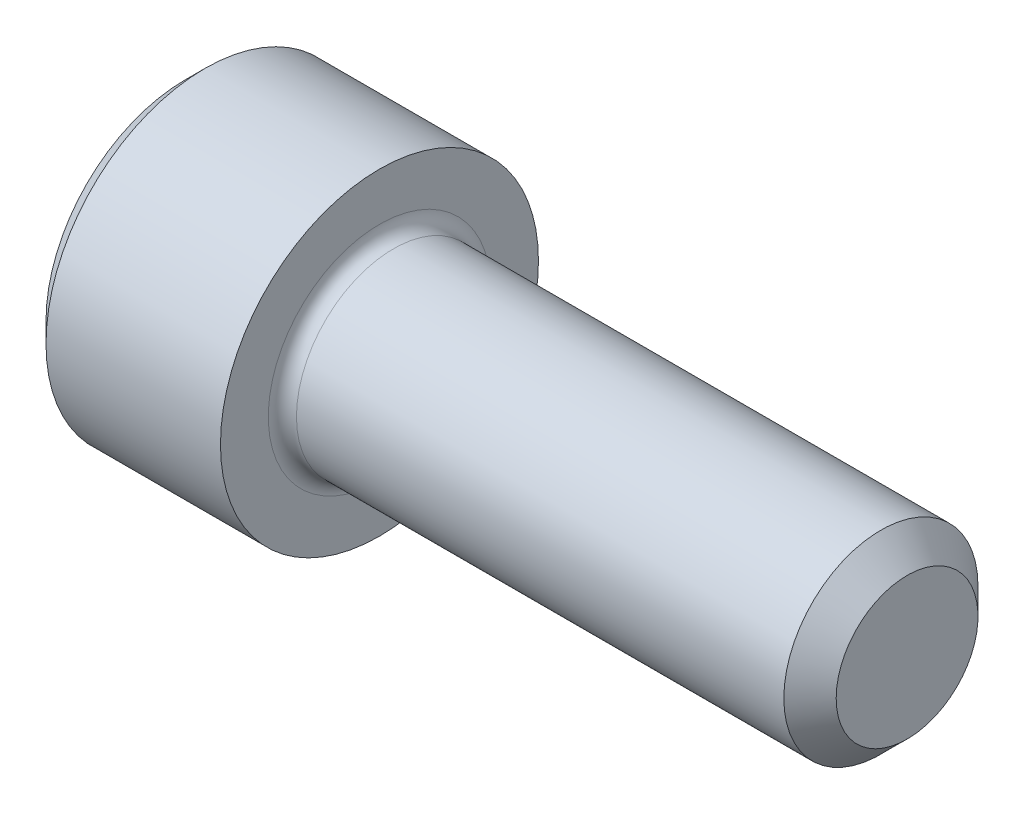
SolidWorks part; units mm, degrees
revolve "Base-Revolve" add sketch "BodySke"
sketch "BodySke" plane through (0, 0, 0) normal (0, 0, 1) x (1, 0, 0)
  line L0 (0, 0) -> (0, 2.5146)
  line L1 (0.3556, 2.8702) -> (3.5052, 2.8702)
  line L2 (3.5052, 2.8702) -> (3.5052, 1.7526)
  line L3 (3.5052, 1.7526) -> (12.5578, 1.7526)
  line L4 (13.0302, 1.2802) -> (13.0302, 0)
  line L5 (13.0302, 0) -> (0, 0)
  line L6 (-31.75, 0) -> (127, 0) construction
  line L7 (0, 2.5146) -> (0.3556, 2.8702)
  line L8 (13.0302, 1.2802) -> (12.5578, 1.7526)
  line L9 (0, -2.5146) -> (0.3556, -2.8702) construction
  line L10 (13.0302, -1.2802) -> (12.5578, -1.7526) construction
  line L11 (4.2977, 9.525) -> (4.2977, 3.175) construction
  line L12 (3.5052, 9.525) -> (3.5052, 3.175) construction
  line L13 (-25.0698, 9.525) -> (-25.0698, 3.175) construction
  dimension "Diameter" = 3.5052
  dimension "Head_ht" = 3.5052
  dimension "Length" = 9.525
  dimension "Body_ch_ang" = 45
  dimension "Head_dia" = 5.7404
  dimension "Head_ch_ang" = 45
  dimension "Head_side_ht" = 3.1496
  dimension "Minor_dia" = 2.5603
  dimension "Advance" = 0.7925
  dimension "Thread_nom" = 9.525
  dimension "Thread_length" = 38.1
cosmetic thread "ThreadCosmetic" [suppressed]
fillet "Fillet1" radius 0.254 1 edges at (3.5052, 0, 1.7526)
ref_plane "Plane1" through (0, 0, 0) normal (0, 0, 1) x (1, 0, 0)
ref_plane "Plane2" through (0, 0, 0) normal (0, 1, 0) x (1, 0, 0)
ref_plane "Plane3" through (0, 0, 0) normal (1, 0, 0) x (0, 0, -1)
sketch "Sketch2" plane through (0, 0, 0) normal (0, 0, 1) x (1, 0, 0)
  line L0 (0, 1.3843) -> (1.6256, 1.3843)
  line L1 (1.6256, 1.3843) -> (2.4248, 0)
  line L2 (-31.75, 0) -> (127, 0) construction
  line L3 (2.4248, 0) -> (0, 0)
  line L4 (0, 0) -> (0, 1.3843)
  line L5 (0, 2.5146) -> (0, -2.5146) construction
  line L6 (0, 0) -> (47.625, 0) construction
  line L7 (3.5052, -2.8702) -> (3.5052, 2.8702) construction
  dimension "D1" = 1.3843
  dimension "D2" = 60
revolve "Hex-PreBroach" cut sketch "Sketch2" angle 360 about L6
sketch "Sketch3" plane through (0, 0, 0) normal (-1, 0, 0) x (0, 0.5, 0.866)
  line L0 (0.7992, 1.3843) -> (-0.7992, 1.3843)
  line L1 (-0.7992, 1.3843) -> (-1.5985, 0)
  line L2 (0.7992, 1.3843) -> (1.5985, 0)
  line L3 (0.7992, -1.3843) -> (1.5985, 0)
  line L4 (0.7992, -1.3843) -> (-0.7992, -1.3843)
  line L5 (-0.7992, -1.3843) -> (-1.5985, 0)
  dimension "D1" = 1.3843
  dimension "D2" = 1.3843
  dimension "Hex_size" = 2.7686
extrude "Hex" cut sketch "Sketch3" against normal blind 1.6256
sketch "Sketch4" plane through (0, 0, 0) normal (-1, 0, 0) x (0, 0, 1)
  line L0 (0, 0) -> (1.7399, 0)
  line L1 (0, 0) -> (6.1484, 3.5498) construction
  line L2 (0, 0) -> (0.8699, 1.5068)
  line L3 (1.4457, 0.3947) -> (1.6607, 0.5189)
  line L4 (1.0647, 1.0546) -> (1.2797, 1.1788)
  arc A0 (1.4457, 0.3947) -> (1.0647, 1.0546) centre (0, 0) ccw
  arc A1 (1.7399, 0) -> (1.6607, 0.5189) centre (0, 0) ccw
  arc A2 (0.8699, 1.5068) -> (1.2797, 1.1788) centre (0, 0) cw
  dimension "D1" = 30
  dimension "D2" = 60
  dimension "Spline_p_dim" = 0.762
  dimension "D3" = 0.381
extrude "Spline" [suppressed] cut sketch "Sketch4" against normal blind 1.6256
pattern_circular "CirPattern1" [suppressed] count 6 every 60
sketch "Sketch5" plane through (0, 0, 0) normal (0, 0, 1) x (1, 0, 0)
  line L0 (-31.75, 0) -> (127, 0) construction
  line L2 (0, 2.5146) -> (0, -2.5146) construction
  circle A0 centre (1.27, 0) radius 0.4445
  dimension "Drilled_hole_dia" = 0.889
  dimension "Drilled_hole_loc" = 1.27
extrude "Hole" [suppressed] cut sketch "Sketch5" against normal through all and the other way through all
pattern_circular "Drilled-4" [suppressed] count 2 every 60
pattern_circular "Drilled-6" [suppressed] count 3 every 60
sketch "ThdSchSke" plane through (0, 0, 0) normal (0, 0, 1) x (1, 0, 0)
  line L0 (4.2977, -1.2802) -> (3.9669, -1.7526)
  line L1 (4.2977, -1.2802) -> (4.6285, -1.7526)
  line L2 (4.6285, -1.7526) -> (4.6285, -2.1907)
  line L3 (-3.175, 0) -> (5.1513, 0) construction
  line L5 (4.6285, -2.1907) -> (3.9669, -2.1907)
  line L6 (3.9669, -2.1907) -> (3.9669, -1.7526)
  line L7 (0, 2.5146) -> (0, -2.5146) construction
  dimension "Thread_minor" = 2.5603
  dimension "Diameter" = 3.5052
  dimension "Start" = 4.2977
revolve "ThreadSchematic" [suppressed] cut sketch "ThdSchSke" angle 360 about L3
pattern_linear "ThdSchPat" [suppressed]
equation "\"D2@Sketch3\" = \"Hex_size@Sketch3\" / 2"
equation "\"D1@Sketch3\" = \"Hex_size@Sketch3\" / 2"
equation "\"D1@Sketch2\" = \"Hex_size@Sketch3\" / 2"
equation "\"D3@Sketch4\" = \"Spline_p_dim@Sketch4\" / 2"
equation "\"Thread_minor@ThreadCosmetic\"  =  \"Minor_dia@BodySke\""
equation "\"D2@CirPattern1\" = 360 / \"Num_teeth@CirPattern1\""
equation "\"Wall_thickness@Sketch2\" = \"Head_ht@BodySke\" - \"Key_eng@Hex\""
equation "\"Thread_length@ThreadCosmetic\" = ((sgn( (\"Length@BodySke\" - \"Advance@BodySke\" ) - \"Thread_nom@BodySke\" )-1)*( (\"Length@BodySke\" - \"Advance@BodySke\" ) - \"Thread_nom@BodySke\" ))/-2+ \"Thread_nom@BodySke\""
equation "\"Thread_minor@ThdSchSke\" = \"Minor_dia@BodySke\""
equation "\"Diameter@ThdSchSke\" = \"Diameter@BodySke\""
equation "\"Overcut@ThdSchSke\" = \"Diameter@BodySke\" * 1.25"
equation "\"Start@ThdSchSke\" = \"Head_ht@BodySke\" + \"Length@BodySke\" - \"Thread_length@ThreadCosmetic\"  '---Non-countersunk---"
equation "\"Num_threads@ThdSchPat\" = int( \"Thread_length@ThreadCosmetic\" / \"Advance@BodySke\" + 0.999 )  + 1"
equation "\"Advance@ThdSchPat\" = \"Thread_length@ThreadCosmetic\" /  (\"Num_threads@ThdSchPat\" - 1) 'relax it"
equation "\"Num_threads@ThdSchPat\" = \"Num_threads@ThdSchPat\" - sgn( \"Num_threads@ThdSchPat\" - 1) '---chamfered tips only---"
